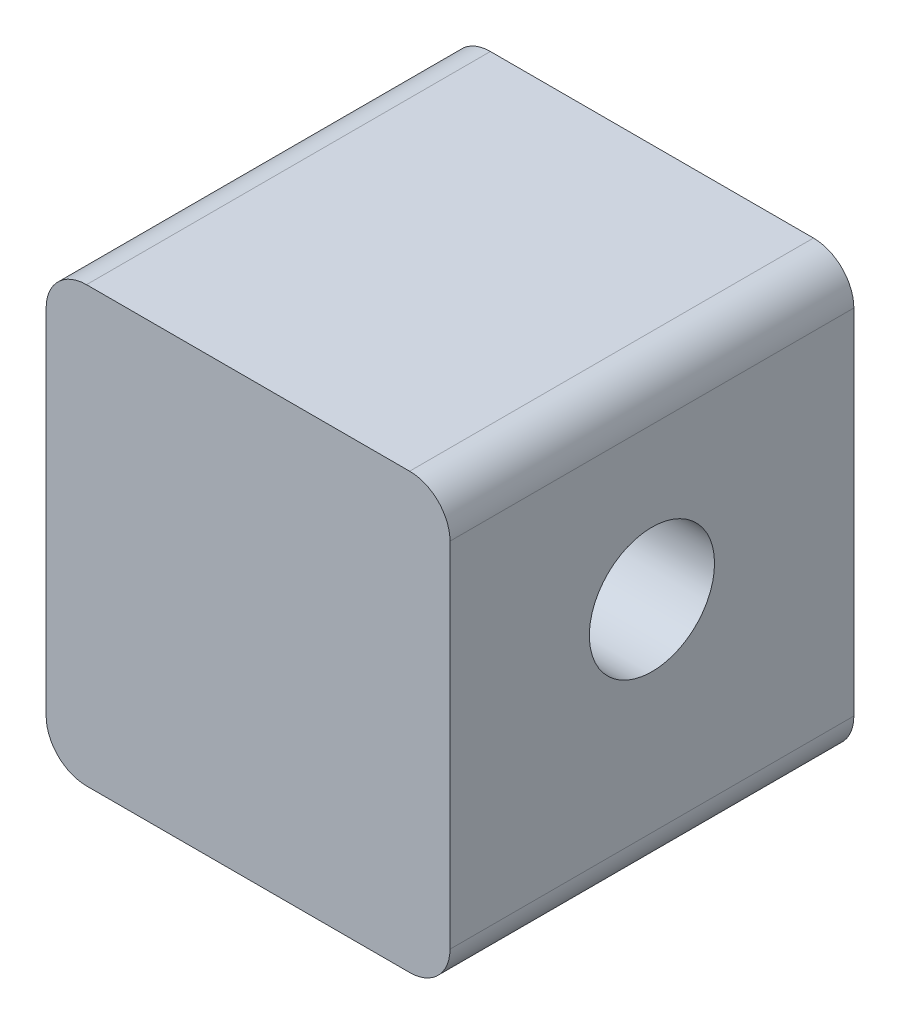
SolidWorks part; units mm, degrees
ref_plane "Front Plane" through (0, 0, 0) normal (0, 0, 1) x (1, 0, 0)
ref_plane "Top Plane" through (0, 0, 0) normal (0, 1, 0) x (1, 0, 0)
ref_plane "Right Plane" through (0, 0, 0) normal (1, 0, 0) x (0, 0, -1)
sketch "Sketch1" plane through (0, 0, 0) normal (0, 0, 1) x (1, 0, 0)
  line L0 (-8, -21.5) -> (8, -21.5)
  line L1 (10, -19.5) -> (10, -2)
  line L2 (8, 0) -> (-8, 0)
  line L3 (-10, -2) -> (-10, -19.5)
  arc A0 (8, -21.5) -> (10, -19.5) centre (8, -19.5) ccw
  arc A1 (10, -2) -> (8, 0) centre (8, -2) ccw
  arc A2 (-8, 0) -> (-10, -2) centre (-8, -2) ccw
  arc A3 (-10, -19.5) -> (-8, -21.5) centre (-8, -19.5) ccw
extrude "Boss-Extrude1" add sketch "Sketch1" along normal mid plane 20
sketch "Sketch2" plane through (0, 0, 0) normal (1, 0, 0) x (0, 0, -1)
  circle A0 centre (0, -9.5) radius 3.1
extrude "Cut-Extrude1" cut sketch "Sketch2" against normal through all and the other way through all
ref_plane "Plane1" through (0, -21.5, 0) normal (0, 1, 0) x (1, 0, 0)
sketch "Sketch3" plane through (0, -21.5, 0) normal (0, 1, 0) x (1, 0, 0)
  circle A0 centre (0, 0) radius 2
extrude "Cut-Extrude2" cut sketch "Sketch3" along normal blind 8.5
